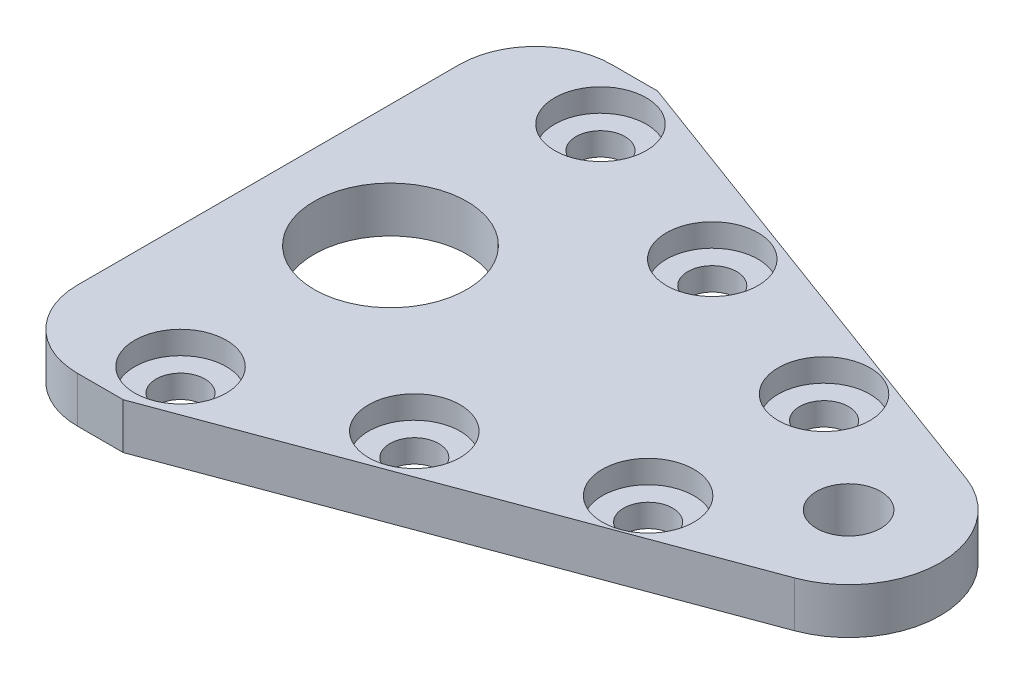
SolidWorks part; units mm, degrees
material "1060 Alloy"
ref_plane "Front Plane" through (0, 0, 0) normal (0, 0, 1) x (1, 0, 0)
ref_plane "Top Plane" through (0, 0, 0) normal (0, 1, 0) x (1, 0, 0)
ref_plane "Right Plane" through (0, 0, 0) normal (1, 0, 0) x (0, 0, -1)
sketch "Sketch1" plane through (0, 0, 0) normal (0, 1, 0) x (1, 0, 0)
  line L0 (0, 0) -> (30, 0) construction
  line L1 (-30, -17.5) -> (30, -17.5)
  line L2 (-30, -17.5) -> (-30, 17.5)
  line L3 (-30, 17.5) -> (30, 17.5)
  line L4 (30, -17.5) -> (30, 17.5)
  line L5 (-30, -17.5) -> (30, 17.5) construction
  line L6 (-30, 17.5) -> (30, -17.5) construction
  line L7 (0, 17.5) -> (0, -17.5) construction
  line L8 (0, 17.5) -> (32.0824, 5.627)
  line L9 (0, -17.5) -> (32.0824, -5.627)
  line L10 (-8, 17.5) -> (-8, -17.5)
  circle A0 centre (0, 0) radius 5
  circle A1 centre (30, 0) radius 2.1
  circle A2 centre (30, 0) radius 6
  point P0 (0, 0)
  dimension "D1" = 10
  dimension "D5" = 4.2
  dimension "D6" = 12
  dimension "D2" = 60
  dimension "D3" = 35
  dimension "D4" = 30
  dimension "D7" = 8
extrude "Boss-Extrude1" add sketch "Sketch1" along normal blind 3 contours A2 L4 L9 | L4 A2 A1 | A2 L8 L4 | A2 L4 L8 L3 L2 L1 L9 A0 | L4 A2 A1
sketch "Sketch3" plane through (0, 3, 0) normal (0, 1, 0) x (1, 0, 0)
  line L0 (0, 13.75) -> (0, -13.75) construction
  line L1 (0, -13.75) -> (39.2829, 0) construction
  line L2 (39.2829, 0) -> (0, 13.75) construction
  line L3 (0, 0) -> (39.2829, 0) construction
  line L4 (-8, 17.5) -> (-8, -17.5) construction
  line L7 (0, 17.5) -> (0, 13.75) construction
  line L8 (0, 13.75) -> (0, -13.75) construction
  line L9 (0, -13.75) -> (0, -17.5) construction
  circle A0 centre (0, 13.75) radius 1.6
  circle A1 centre (11.3154, 9.7549) radius 1.6
  circle A2 centre (22.6309, 5.7598) radius 1.6
  circle A3 centre (22.6309, -5.7598) radius 1.6
  circle A4 centre (0, -13.75) radius 1.6
  circle A5 centre (11.3154, -9.7549) radius 1.6
  dimension "D2" = 3.2
  dimension "D1" = 3.75
  dimension "D4" = 3.75
  dimension "D3" = 3
extrude "Cut-Extrude1" cut sketch "Sketch3" against normal blind 10
fillet "Fillet1" radius 5 2 edges at (-8, 1.5, 17.5) (-8, 1.5, -17.5)
sketch "Sketch4" plane through (0, 3, 0) normal (0, 1, 0) x (1, 0, 0)
  circle A0 centre (0, 13.75) radius 3
  circle A1 centre (11.3154, 9.7549) radius 3
  circle A2 centre (22.6309, 5.7598) radius 3
  circle A3 centre (22.6309, -5.7598) radius 3
  circle A4 centre (11.3154, -9.7549) radius 3
  circle A5 centre (0, -13.75) radius 3
  dimension "D1" = 6
extrude "Cut-Extrude2" cut sketch "Sketch4" against normal blind 1.5
